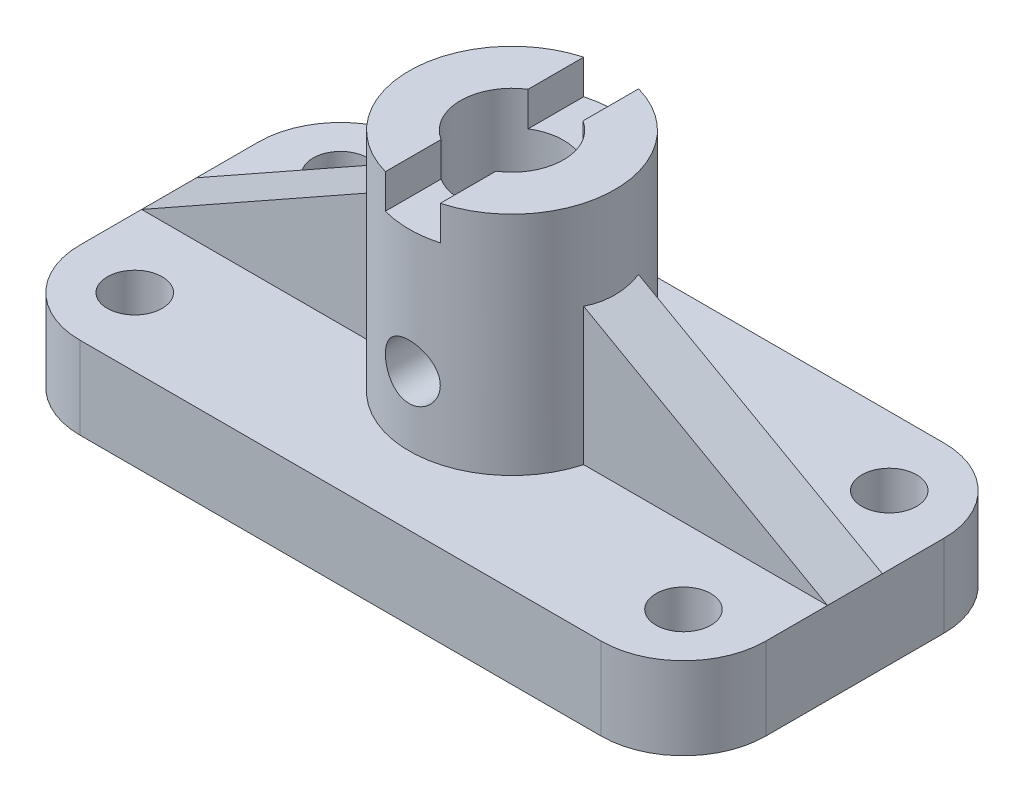
SolidWorks part; units mm, degrees
ref_plane "前视基准面" through (0, 0, 0) normal (0, 0, 1) x (1, 0, 0)
ref_plane "上视基准面" through (0, 0, 0) normal (0, 1, 0) x (1, 0, 0)
ref_plane "右视基准面" through (0, 0, 0) normal (1, 0, 0) x (0, 0, -1)
other "Configuration Table"
sketch "草图1" plane through (0, 0, 0) normal (0, 1, 0) x (1, 0, 0)
  line L1 (38, 25) -> (-38, 25)
  line L2 (50, 13) -> (50, -13)
  line L3 (38, -25) -> (-38, -25)
  line L4 (-50, 13) -> (-50, -13)
  line L5 (50, 25) -> (-50, -25) construction
  line L6 (50, -25) -> (-50, 25) construction
  arc A0 (-38, -25) -> (-50, -13) centre (-38, -13) cw
  arc A1 (50, -13) -> (38, -25) centre (38, -13) cw
  arc A2 (38, 25) -> (50, 13) centre (38, 13) cw
  arc A3 (-38, 25) -> (-50, 13) centre (-38, 13) ccw
  point P0 (0, 0)
  dimension "D3" = 12
  dimension "D1" = 100
  dimension "D2" = 50
extrude "凸台-拉伸1" add sketch "草图1" along normal blind 12
sketch "草图2" plane through (0, 12, 0) normal (0, 1, 0) x (1, 0, 0)
  line L0 (-68.8055, 0) -> (68.8055, 0) construction
  line L1 (0, -42.9184) -> (0, 42.9184) construction
  circle A0 centre (-40, -15) radius 4
  circle A5 centre (40, -15) radius 4
  circle A6 centre (40, 15) radius 4
  circle A7 centre (-40, 15) radius 4
  point P5 (0, 0)
  point P11 (0, 0)
  dimension "D3" = 8
  dimension "D1" = 15
  dimension "D4" = 40
extrude "切除-拉伸2" cut sketch "草图2" against normal through all
sketch "草图4" plane through (0, 12, 0) normal (0, 1, 0) x (1, 0, 0)
  line L0 (-50, -4) -> (-14.4568, -4)
  line L5 (-74.808, 0) -> (74.808, 0) construction
  line L6 (-50, 4) -> (-14.4568, 4)
  line L10 (-50, 4) -> (-50, -4)
  line L11 (-50, 13) -> (-50, -13) construction
  line L12 (14.4568, 4) -> (50, 4)
  line L13 (50, -13) -> (50, 13) construction
  line L14 (14.4568, -4) -> (50, -4)
  line L15 (50, 4) -> (50, -4)
  arc A0 (-14.4568, -4) -> (14.4568, -4) centre (0, 0) ccw
  arc A1 (14.4568, 4) -> (-14.4568, 4) centre (0, 0) ccw
  point P6 (0, 0)
  dimension "D1" = 30
  dimension "D2" = 4
  dimension "D3" = 4
extrude "凸台-拉伸2" add sketch "草图4" along normal blind 20
sketch "草图5" plane through (0, 0, 4) normal (0, 0, 1) x (1, 0, 0)
  line L0 (-14.4568, 32) -> (-50, 12)
  line L1 (-50, 12) -> (-50, 32)
  line L2 (-50, 32) -> (-50, 12) construction
  line L3 (-50, 32) -> (-14.4568, 32) construction
  line L4 (-50, 32) -> (-14.4568, 32)
extrude "切除-拉伸3" cut sketch "草图5" against normal through all
sketch "草图6" plane through (0, 0, 4) normal (0, 0, 1) x (1, 0, 0)
  line L0 (14.4568, 32) -> (50, 12)
  line L1 (50, 12) -> (50, 32)
  line L2 (50, 32) -> (14.4568, 32)
extrude "切除-拉伸4" cut sketch "草图6" against normal through all
sketch "草图7" plane through (0, 32, 0) normal (0, 1, 0) x (1, 0, 0)
  circle A0 centre (0, 0) radius 7.5
  dimension "D1" = 15
extrude "切除-拉伸5" cut sketch "草图7" against normal through all
sketch "草图8" plane through (0, 32, 0) normal (0, 1, 0) x (1, 0, 0)
  circle A0 centre (0, 0) radius 7.5
  circle A1 centre (0, 0) radius 15
extrude "凸台-拉伸3" add sketch "草图8" against normal blind 20
sketch "草图10" plane through (0, 32, 0) normal (0, 1, 0) x (1, 0, 0)
  circle A0 centre (0, 0) radius 7.5
  circle A1 centre (0, 0) radius 15
extrude "凸台-拉伸4" add sketch "草图10" along normal blind 13
sketch "草图11" plane through (0, 45, 0) normal (0, 1, 0) x (1, 0, 0)
  line L0 (0, 16.2964) -> (0, -16.2964) construction
  line L1 (4, -6.3443) -> (4, -14.4568)
  line L2 (4, 6.3443) -> (4, 14.4568)
  line L3 (-4, -6.3443) -> (-4, -14.4568)
  line L4 (-4, 6.3443) -> (-4, 14.4568)
  arc A0 (4, 6.3443) -> (4, -6.3443) centre (0, 0) cw
  circle A1 centre (0, 0) radius 7.5 construction
  arc A2 (4, 14.4568) -> (4, -14.4568) centre (0, 0) cw
  circle A3 centre (0, 0) radius 15 construction
  arc A4 (-4, 6.3443) -> (-4, -6.3443) centre (0, 0) ccw
  arc A5 (-4, 14.4568) -> (-4, -14.4568) centre (0, 0) ccw
  point P4 (0, 0)
  dimension "D1" = 4
extrude "切除-拉伸7" cut sketch "草图11" against normal blind 5 flip side to cut
sketch "草图12" plane through (0, 0, 0) normal (0, 0, 1) x (1, 0, 0)
  line L0 (14.4568, 12) -> (-14.4568, 12) construction
  circle A0 centre (0, 22) radius 4
  point P2 (0, 25.0435)
  dimension "D2" = 8
  dimension "D1" = 10
extrude "切除-拉伸8" cut sketch "草图12" against normal through all and the other way through all
